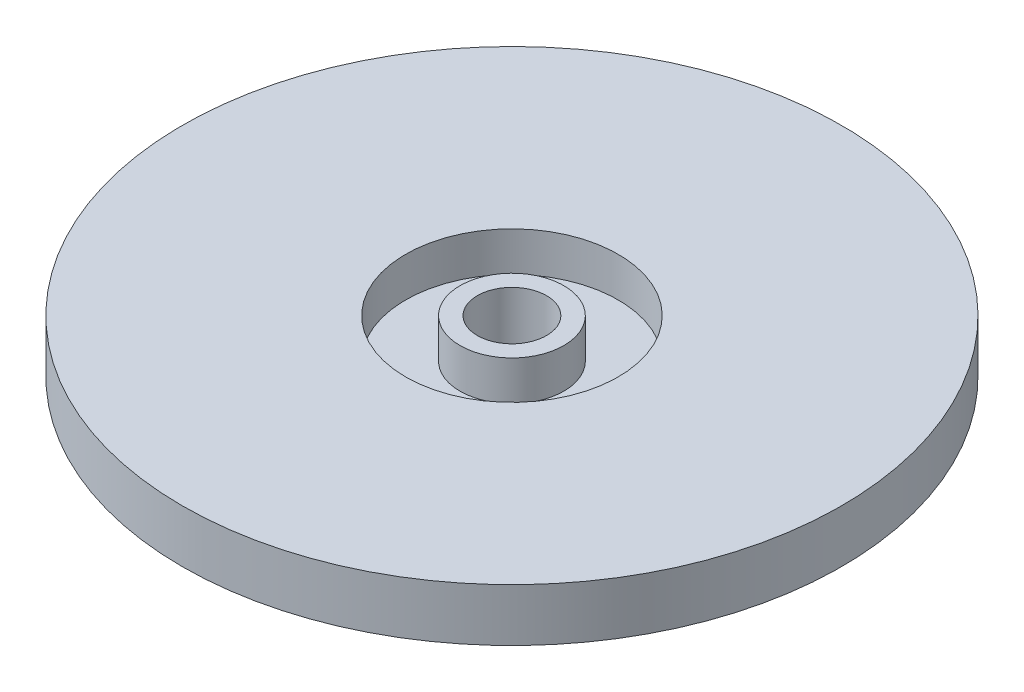
SolidWorks part; units mm, degrees
ref_plane "Front Plane" through (0, 0, 0) normal (0, 0, 1) x (1, 0, 0)
ref_plane "Top Plane" through (0, 0, 0) normal (0, 1, 0) x (1, 0, 0)
ref_plane "Right Plane" through (0, 0, 0) normal (1, 0, 0) x (0, 0, -1)
sketch "Sketch1" plane through (0, 0, 0) normal (0, 1, 0) x (1, 0, 0)
  line L0 (0, 0) -> (-15.026, 15.026) construction
  line L1 (0, 0) -> (0, 21.25) construction
  line L2 (-9.9505, 0) -> (10.9328, 0) construction
  line L4 (47, -50) -> (-47, -50) construction
  line L5 (50, -47) -> (50, 47) construction
  line L6 (47, 50) -> (-47, 50) construction
  line L7 (-50, -47) -> (-50, 47) construction
  line L8 (50, -50) -> (-50, 50) construction
  line L9 (50, 50) -> (-50, -50) construction
  circle A0 centre (0, 0) radius 50
  circle A1 centre (0, -21.25) radius 2.25 construction
  circle A2 centre (-15.026, -15.026) radius 2.25 construction
  circle A3 centre (-21.25, 0) radius 2.25 construction
  circle A4 centre (-15.026, 15.026) radius 2.25 construction
  circle A5 centre (0, 21.25) radius 2.25 construction
  circle A6 centre (15.026, 15.026) radius 2.25 construction
  circle A7 centre (21.25, 0) radius 2.25 construction
  circle A8 centre (15.026, -15.026) radius 2.25 construction
  circle A9 centre (0, 0) radius 21.25 construction
  arc A10 (50, -47) -> (47, -50) centre (47, -47) cw construction
  arc A11 (-50, -47) -> (-47, -50) centre (-47, -47) ccw construction
  arc A12 (-50, 47) -> (-47, 50) centre (-47, 47) cw construction
  arc A13 (50, 47) -> (47, 50) centre (47, 47) ccw construction
  dimension "D1" = 100
  dimension "D2" = 4.5
  dimension "D3" = 42.5
  dimension "D7" = 3
  dimension "D4" = 45
  dimension "D5" = 30.052
  dimension "D6" = 100
extrude "Boss-Extrude1" add sketch "Sketch1" along normal mid plane 8
sketch "Sketch2" plane through (0, 4, 0) normal (0, 1, 0) x (1, 0, 0)
  line L0 (0, 22.5364) -> (0, -22.5364) construction
  line L3 (-25, 0) -> (25, 0) construction
  circle A0 centre (0, 0) radius 16.125
  circle A1 centre (0, 0) radius 7.875
  dimension "D1" = 32.25
  dimension "D2" = 15.75
extrude "Cut-Extrude1" cut sketch "Sketch2" against normal blind 6
sketch "Sketch3" plane through (0, 4, 0) normal (0, 1, 0) x (1, 0, 0)
  circle A0 centre (0, 0) radius 5.25
  dimension "D1" = 10.5
extrude "Cut-Extrude2" cut sketch "Sketch3" against normal through all
sketch "Sketch4" plane through (0, -4, 0) normal (0, -1, 0) x (1, 0, 0)
  circle A0 centre (0, 0) radius 10.25
  circle A1 centre (0, 0) radius 15.25
  dimension "D1" = 30.5
  dimension "D2" = 20.5
extrude "Boss-Extrude2" add sketch "Sketch4" along normal blind 20
